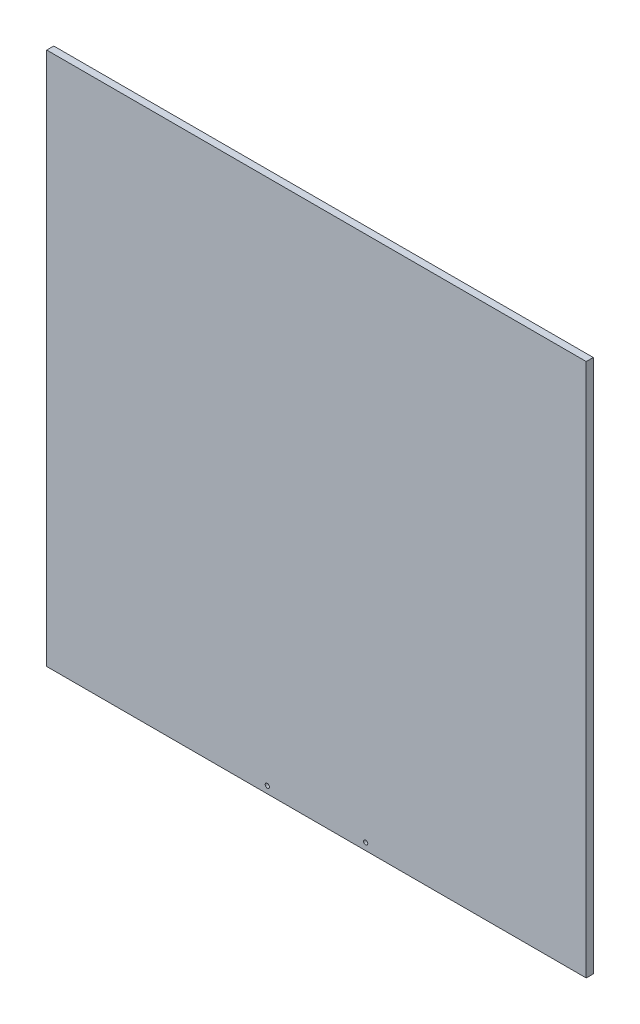
SolidWorks part; units mm, degrees
ref_plane "Plan de face" through (0, 0, 0) normal (0, 0, 1) x (1, 0, 0)
ref_plane "Plan de dessus" through (0, 0, 0) normal (0, 1, 0) x (1, 0, 0)
ref_plane "Plan de droite" through (0, 0, 0) normal (1, 0, 0) x (0, 0, -1)
sketch "Esquisse1" plane through (0, 0, 0) normal (0, 0, 1) x (1, 0, 0)
  line L0 (-200, 0) -> (200, 0) construction
  line L1 (-192, 190) -> (192, 190)
  line L2 (-192, 190) -> (-192, 97.5)
  line L3 (-192, -190) -> (192, -190)
  line L4 (192, 190) -> (192, 97.5)
  line L5 (-192, 190) -> (192, -190) construction
  line L6 (-192, -190) -> (192, 190) construction
  line L17 (0, 190) -> (0, -190) construction
  line L26 (-192, 97.5) -> (-192, -87.5)
  line L27 (-192, -87.5) -> (-192, -190)
  line L28 (192, -107.5) -> (192, -190)
  line L29 (192, 97.5) -> (192, -107.5)
  point P0 (0, 0)
  point P6 (-202.5, 92.5)
  point P9 (0, 0)
  dimension "D1" = 384
  dimension "D2" = 380
extrude "Boss.-Extru.1" add sketch "Esquisse1" along normal blind 5
sketch "Esquisse3" plane through (0, 0, 0) normal (0, 0, -1) x (-1, 0, 0)
  circle A0 centre (35, -185) radius 1.5
  circle A1 centre (-35, -185) radius 1.5
extrude "Enlèv. mat.-Extru.2" cut sketch "Esquisse3" against normal through all
